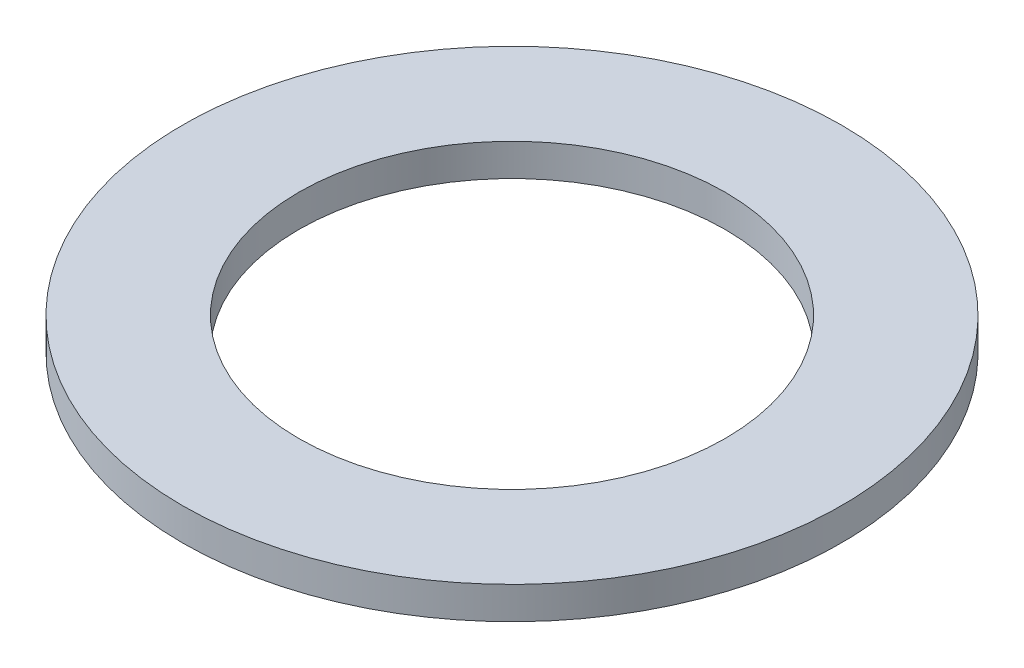
SolidWorks part; units mm, degrees
ref_plane "Front Plane" through (0, 0, 0) normal (0, 0, 1) x (1, 0, 0)
ref_plane "Top Plane" through (0, 0, 0) normal (0, 1, 0) x (1, 0, 0)
ref_plane "Right Plane" through (0, 0, 0) normal (1, 0, 0) x (0, 0, -1)
sketch "Sketch1" plane through (0, 0, 0) normal (0, 0, 1) x (1, 0, 0)
  line L0 (0, -200) -> (0, 100) construction
  line L1 (3.3, 2) -> (3.3, 2.5)
  line L2 (3.3, 2.5) -> (5.1, 2.5)
  line L3 (5.1, 2.5) -> (5.1, 2)
  line L4 (5.1, 2) -> (3.3, 2)
revolve "Revolve1" add sketch "Sketch1" angle 360 about L0
